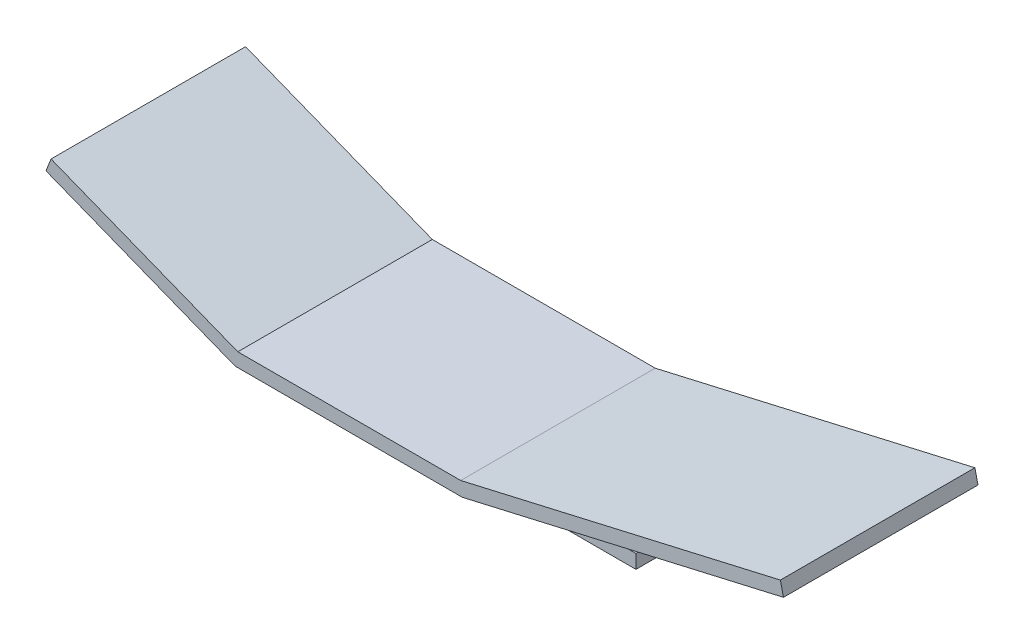
SolidWorks part; units mm, degrees
ref_plane "Front Plane" through (0, 0, 0) normal (0, 0, 1) x (1, 0, 0)
ref_plane "Top Plane" through (0, 0, 0) normal (0, 1, 0) x (1, 0, 0)
ref_plane "Right Plane" through (0, 0, 0) normal (1, 0, 0) x (0, 0, -1)
sketch "Esboço1" plane through (0, 0, 30) normal (0, 0, 1) x (1, 0, 0)
  line L1 (-9.0352, 701.5167) -> (511.6139, 701.5167)
  line L2 (-9.0352, 701.5167) -> (-9.0352, 684.5167)
  line L3 (-9.0352, 684.5167) -> (511.6139, 684.5167)
  line L4 (511.6139, 701.5167) -> (511.6139, 684.5167)
sketch "Esboço2" plane through (0, 0, 30) normal (0, 0, 1) x (1, 0, 0)
  line L0 (0, 972.24) -> (230.4012, 881.434)
  line L1 (230.4012, 881.434) -> (505.4012, 881.434)
  line L2 (505.4012, 881.434) -> (899.8182, 972.24)
  line L3 (-6.2334, 956.4241) -> (227.172, 864.434)
  line L4 (227.172, 864.434) -> (507.3329, 864.434)
  line L5 (507.3329, 864.434) -> (903.6323, 955.6734)
  line L6 (-6.2334, 956.4241) -> (0, 972.24)
  line L7 (903.6323, 955.6734) -> (899.8182, 972.24)
  dimension "D1" = 17
extrude "Ressalto-extrusão1" add sketch "Esboço1" along normal blind 30
extrude "Ressalto-extrusão2" add sketch "Esboço2" along normal blind 240 separate body
